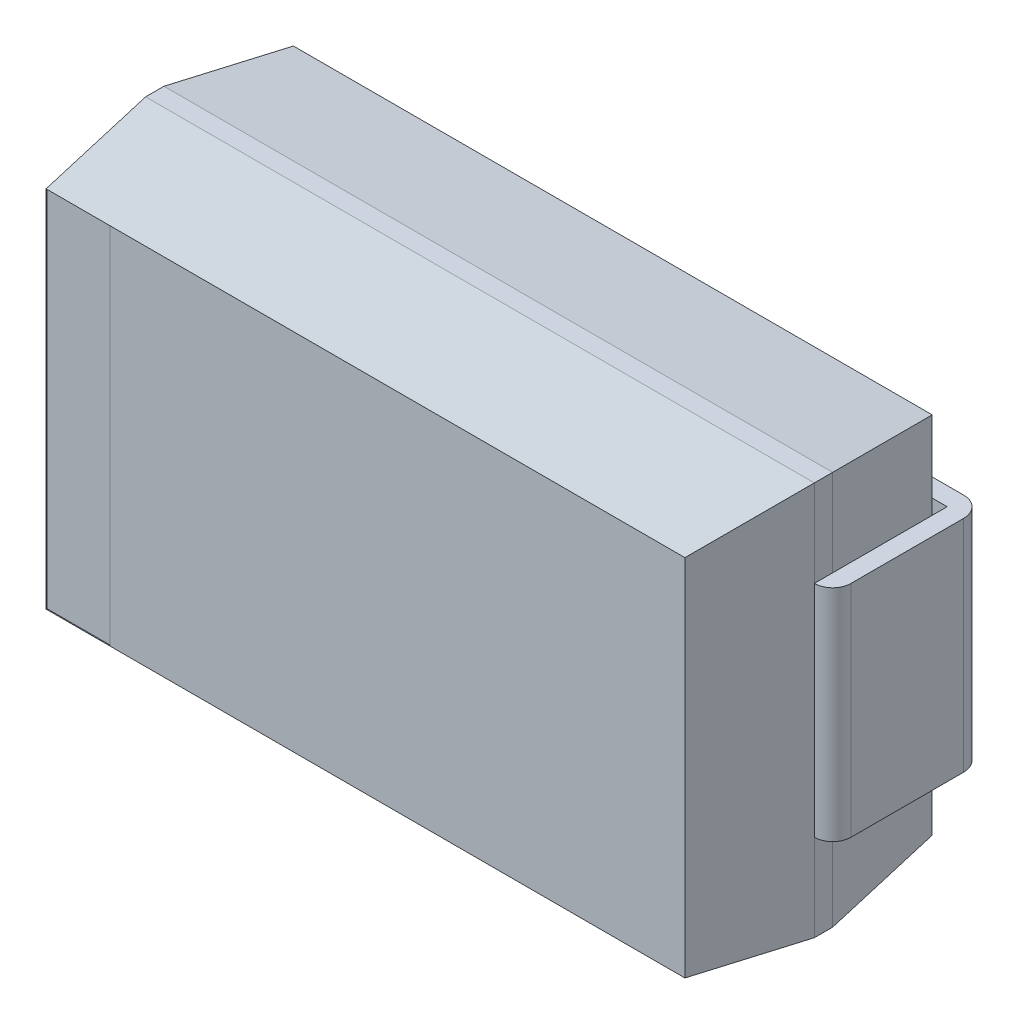
SolidWorks part; units mm, degrees
other "Детальный элемент1"
ref_plane "Спереди" through (0, 0, 0) normal (0, 0, 1) x (1, 0, 0)
ref_plane "Сверху" through (0, 0, 0) normal (0, 1, 0) x (1, 0, 0)
ref_plane "Справа" through (0, 0, 0) normal (1, 0, 0) x (0, 0, -1)
ref_plane "Плоскость1" through (0, 0, 0.2) normal (0, 0, 1) x (1, 0, 0)
sketch "Эскиз1" plane through (0, 0, 0.2) normal (0, 0, 1) x (1, 0, 0)
  line L1 (-3.65, 2.15) -> (3.65, 2.15)
  line L2 (-3.65, 2.15) -> (-3.65, -2.15)
  line L3 (-3.65, -2.15) -> (3.65, -2.15)
  line L4 (3.65, 2.15) -> (3.65, -2.15)
  line L5 (-3.65, 2.15) -> (3.65, -2.15) construction
  line L6 (-3.65, -2.15) -> (3.65, 2.15) construction
  point P0 (0, 0)
  dimension "D1" = 7.3
  dimension "D2" = 4.3
extrude "Бобышка-Вытянуть1" add sketch "Эскиз1" along normal blind 2.7
chamfer "Фаска1" distance 1.25 distance2 0.163 4 edges at (0, 2.15, 2.9) (3.65, 0, 2.9) (0, -2.15, 2.9) (-3.65, 0, 2.9)
chamfer "Фаска2" distance 0.163 distance2 1.25 4 edges at (3.65, 0, 0.2) (0, 2.15, 0.2) (0, -2.15, 0.2) (-3.65, 0, 0.2)
sketch "Эскиз2" plane through (0, 0, 0) normal (0, 1, 0) x (1, 0, 0)
  line L0 (-3.65, -0.2) -> (-3.65, -1.45)
  line L1 (-2.55, 0) -> (-3.63, 0)
  line L2 (-2.55, 0) -> (-2.55, -0.2)
  line L3 (-2.55, -0.2) -> (-3.65, -0.2)
  line L4 (-3.65, -1.45) -> (-3.65, -1.65)
  line L5 (-3.85, -1.45) -> (-3.85, -0.22)
  arc A2 (-3.65, -1.65) -> (-3.85, -1.45) centre (-3.65, -1.45) cw
  arc A3 (-3.63, 0) -> (-3.85, -0.22) centre (-3.63, -0.22) ccw
  dimension "D3" = 0.22
  dimension "D1" = 0.2
  dimension "D2" = 0.2
  dimension "D4" = 1.3
extrude "Бобышка-Вытянуть2" add sketch "Эскиз2" along normal blind 1.2 and the other way blind 1.2 separate body
mirror "Зеркальное отражение1" about plane through (0, 0, 0) normal (1, 0, 0) of bodies 108
sketch "Эскиз3" plane through (0, 0, 2.9) normal (0, 0, 1) x (1, 0, 0)
  line L0 (3.487, 1.987) -> (-3.487, 1.987) construction
  line L1 (-3.487, -1.987) -> (-2.787, -1.987)
  line L2 (-3.487, -1.987) -> (-3.487, 1.987)
  line L3 (-3.487, 1.987) -> (-2.787, 1.987)
  line L4 (-2.787, -1.987) -> (-2.787, 1.987)
  dimension "D1" = 0.7
extrude "Вырез-Вытянуть1" cut sketch "Эскиз3" against normal blind 0.01
